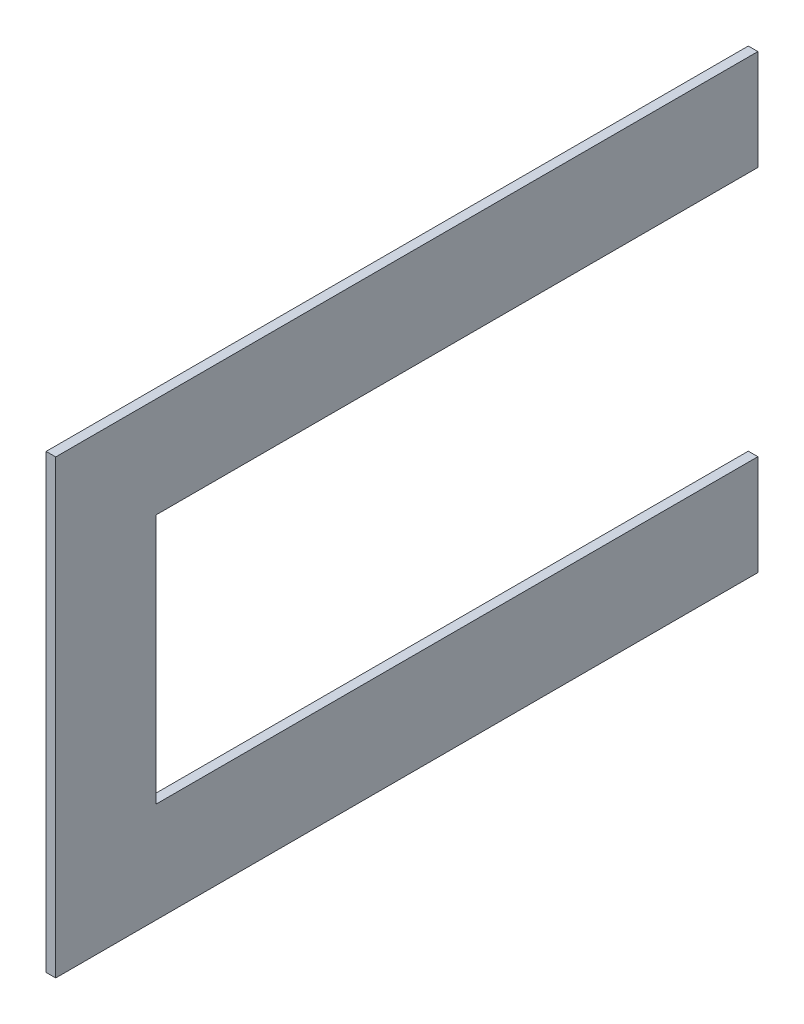
SolidWorks part; units mm, degrees
ref_plane "Front Plane" through (0, 0, 0) normal (0, 0, 1) x (1, 0, 0)
ref_plane "Top Plane" through (0, 0, 0) normal (0, 1, 0) x (1, 0, 0)
ref_plane "Right Plane" through (0, 0, 0) normal (1, 0, 0) x (0, 0, -1)
sketch "Sketch1" plane through (0, 0, 0) normal (1, 0, 0) x (0, 0, -1)
  line L0 (-31.1793, 22.4771) -> (-31.1793, 41.6287)
  line L1 (-50.3309, 41.6287) -> (83.616, 41.6287)
  line L2 (-50.3309, 41.6287) -> (-50.3309, -44.4519)
  line L3 (-50.3309, -44.4519) -> (83.616, -44.4519)
  line L4 (83.616, 41.6287) -> (83.616, -44.4519)
  line L5 (-31.1793, -25.3003) -> (83.616, -25.3003)
  line L6 (-31.1793, -25.3003) -> (-31.1793, 22.4771)
  line L7 (-31.1793, 22.4771) -> (83.616, 22.4771)
  line L8 (83.616, -25.3003) -> (83.616, 22.4771)
  line L9 (-31.1793, -25.3003) -> (-31.1793, -44.4519)
  line L10 (-31.1793, -25.3003) -> (-50.3309, -25.3003)
  dimension "D1" = 86.0806
  dimension "D2" = 133.9469
  dimension "D3" = 19.1516
  dimension "D4" = 19.1516
  dimension "D5" = 19.1516
  dimension "D6" = 47.7774
  dimension "D7" = 114.7953
extrude "Boss-Extrude1" add sketch "Sketch1" along normal blind 1.8288 contours L10 L6 L0 L1 L2 | L0 L7 L4 L1 | L5 L9 L3 L4 | L9 L10 L2 L3
